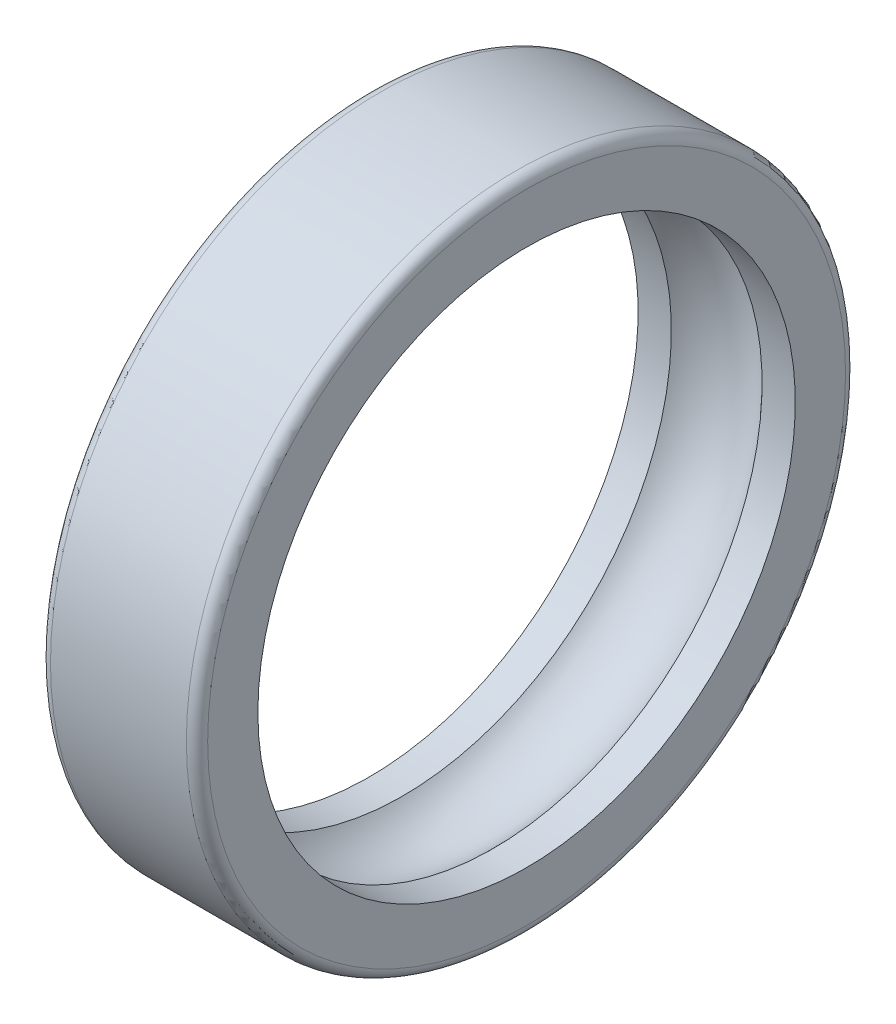
SolidWorks part; units mm, degrees
material "AISI 304"
ref_plane "Front Plane" through (0, 0, 0) normal (0, 0, 1) x (1, 0, 0)
ref_plane "Top Plane" through (0, 0, 0) normal (0, 1, 0) x (1, 0, 0)
ref_plane "Right Plane" through (0, 0, 0) normal (1, 0, 0) x (0, 0, -1)
sketch "Sketch1" plane through (0, 0, 0) normal (0, 0, 1) x (1, 0, 0)
  line L0 (-16.5764, 0) -> (33.1528, 0) construction
  line L1 (0, 53) -> (0, 0) construction
  line L2 (-15.5, 65) -> (15.5, 65)
  line L3 (-15.5, 65) -> (-15.5, 53)
  line L4 (-15.5, 53) -> (-8.9443, 53)
  line L5 (15.5, 65) -> (15.5, 53)
  line L6 (-15.5, 65) -> (15.5, 53) construction
  line L7 (-15.5, 53) -> (15.5, 65) construction
  line L8 (8.9443, 53) -> (15.5, 53)
  arc A0 (-8.9443, 53) -> (8.9443, 53) centre (0, 45) cw
  point P3 (0, 59)
  dimension "D5" = 12
  dimension "D1" = 31
  dimension "D2" = 53
  dimension "D3" = 65
  dimension "D4" = 8
revolve "Revolve1" add sketch "Sketch1" angle 360 about L0
fillet "Fillet1" radius 2.1 2 edges at (15.5, 0, 65) (-15.5, 0, 65)
scale "Scale1" scale about centroid uniform scaling yes scale factor 0.1
